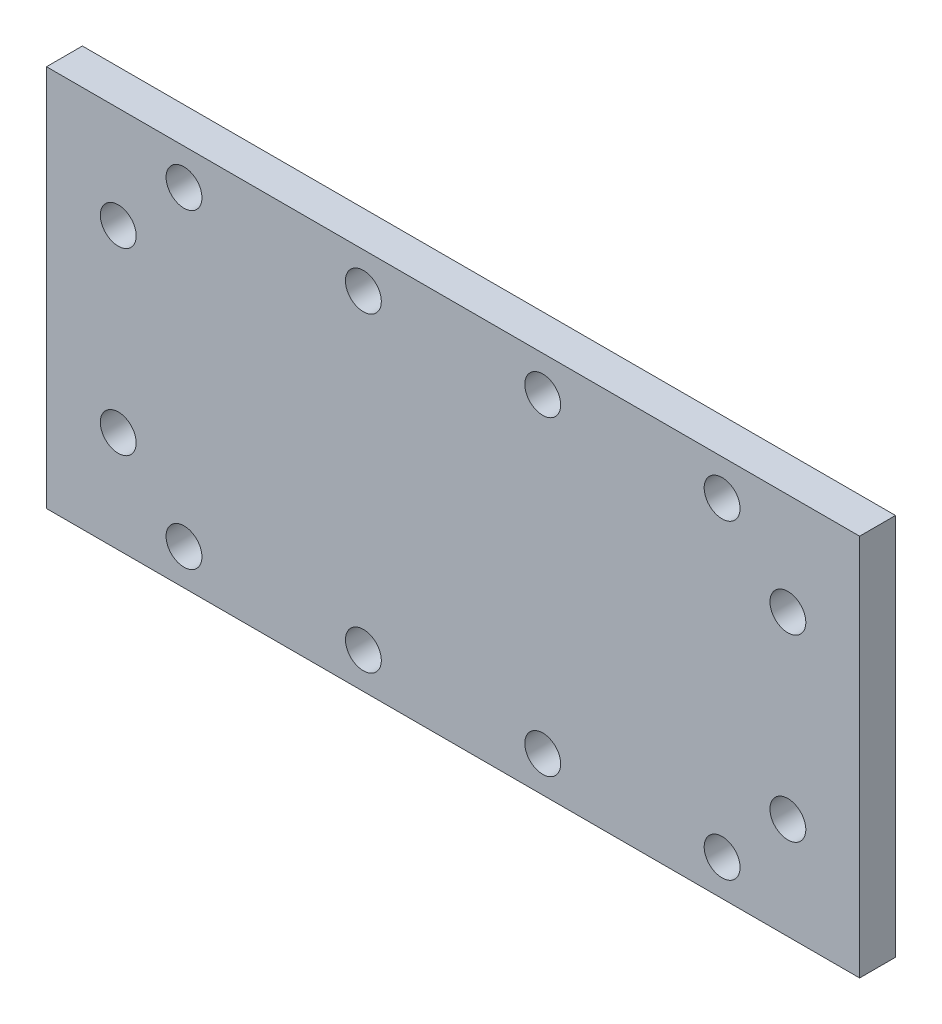
SolidWorks part; units mm, degrees
ref_plane "Front Plane" through (0, 0, 0) normal (0, 0, 1) x (1, 0, 0)
ref_plane "Top Plane" through (0, 0, 0) normal (0, 1, 0) x (1, 0, 0)
ref_plane "Right Plane" through (0, 0, 0) normal (1, 0, 0) x (0, 0, -1)
sketch "Sketch1" plane through (0, 0, 0) normal (0, 0, 1) x (1, 0, 0)
  line L1 (34, -16) -> (-34, -16)
  line L2 (34, -16) -> (34, 16)
  line L3 (34, 16) -> (-34, 16)
  line L4 (-34, -16) -> (-34, 16)
  line L5 (34, -16) -> (-34, 16) construction
  line L6 (34, 16) -> (-34, -16) construction
  point P0 (0, 0)
  point P5 (0, 0)
  dimension "D1" = 68
  dimension "D2" = 32
extrude "Boss-Extrude1" add sketch "Sketch1" along normal blind 3
sketch "Sketch2" plane through (0, 0, 3) normal (0, 0, 1) x (1, 0, 0)
  line L0 (0, 16) -> (0, 0) construction
  line L1 (34, 16) -> (-34, 16) construction
  line L2 (0, 0) -> (-34, 0) construction
  line L3 (-34, 16) -> (-34, -16) construction
  line L5 (-34, -16) -> (34, -16) construction
  circle A0 centre (-22.5, 13) radius 1.5
  circle A1 centre (-7.5, 13) radius 1.5
  circle A2 centre (7.5, 13) radius 1.5
  circle A3 centre (22.5, 13) radius 1.5
  circle A4 centre (-22.5, -13) radius 1.5
  circle A5 centre (22.5, -13) radius 1.5
  circle A6 centre (7.5, -13) radius 1.5
  circle A7 centre (-7.5, -13) radius 1.5
  circle A8 centre (-28, 7.5) radius 1.5
  circle A9 centre (-28, -7.5) radius 1.5
  circle A10 centre (28, -7.5) radius 1.5
  circle A11 centre (28, 7.5) radius 1.5
  point P30 (0, 0)
  dimension "D1" = 3
  dimension "D7" = 3
  dimension "D8" = 3
  dimension "D2" = 11.5
  dimension "D3" = 3
  dimension "D4" = 15
  dimension "D5" = 15
  dimension "D6" = 15
  dimension "D9" = 8.5
  dimension "D10" = 6
  dimension "D11" = 8.5
extrude "Cut-Extrude1" cut sketch "Sketch2" against normal through all
